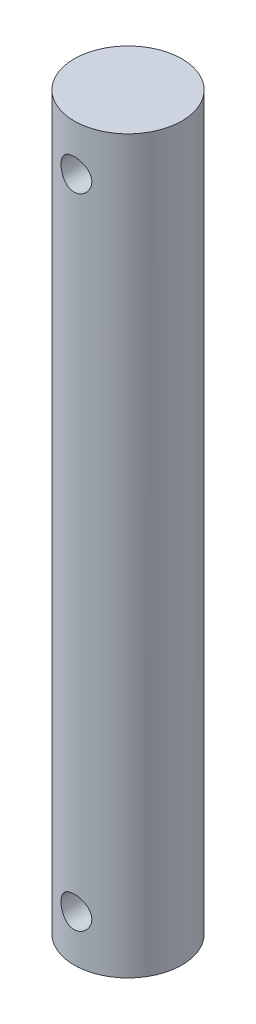
SolidWorks part; units mm, degrees
ref_plane "Спереди" through (0, 0, 0) normal (0, 0, 1) x (1, 0, 0)
ref_plane "Сверху" through (0, 0, 0) normal (0, 1, 0) x (1, 0, 0)
ref_plane "Справа" through (0, 0, 0) normal (1, 0, 0) x (0, 0, -1)
sketch "Эскиз1" plane through (0, 0, 0) normal (0, 1, 0) x (1, 0, 0)
  circle A0 centre (0, 0) radius 3.5
extrude "Вытянуть1" add sketch "Эскиз1" along normal blind 54.5
sketch "Эскиз2" plane through (0, 0, 0) normal (0, 0, 1) x (1, 0, 0)
  line L0 (3.5, 54.5) -> (-3.5, 54.5) construction
  line L1 (3.85, 0) -> (-3.85, 0) construction
  circle A0 centre (0, 48.5) radius 1
  circle A1 centre (0, 7) radius 1
  dimension "D1" = 6
  dimension "D2" = 7
extrude "Вытянуть2" cut sketch "Эскиз2" against normal mid plane 54.5
sketch "Эскиз3" plane through (0, 54.5, 0) normal (0, 1, 0) x (1, 0, 0)
  circle A0 centre (0, 0) radius 7.0709
extrude "Вытянуть3" cut sketch "Эскиз3" against normal blind 3
sketch "Эскиз4" plane through (0, 0, 0) normal (0, -1, 0) x (1, 0, 0)
  circle A0 centre (0, 0) radius 6.0455
extrude "Вытянуть4" cut sketch "Эскиз4" against normal blind 4
